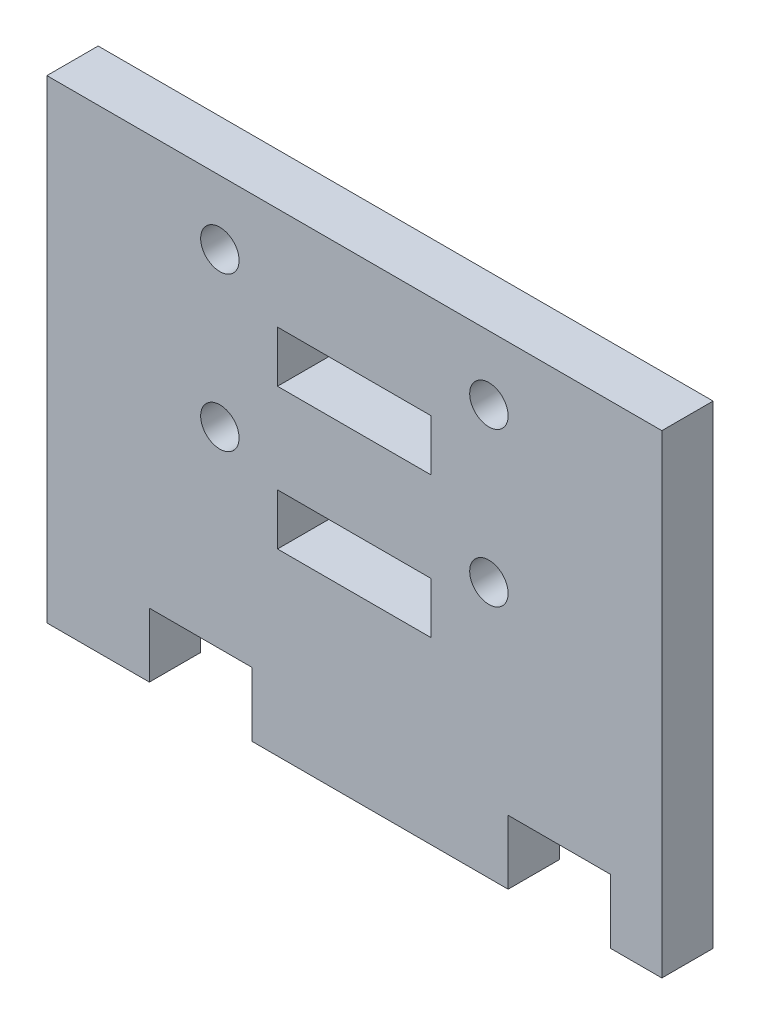
SolidWorks part; units mm, degrees
ref_plane "Front Plane" through (0, 0, 0) normal (0, 0, 1) x (1, 0, 0)
ref_plane "Top Plane" through (0, 0, 0) normal (0, 1, 0) x (1, 0, 0)
ref_plane "Right Plane" through (0, 0, 0) normal (1, 0, 0) x (0, 0, -1)
sketch "Sketch1" plane through (0, 0, 0) normal (0, 0, 1) x (1, 0, 0)
  line L0 (4, 2.5) -> (8, 2.5)
  line L1 (4, 0) -> (0, 0)
  line L2 (0, 18.5) -> (24, 18.5)
  line L3 (0, 0) -> (0, 18.5)
  line L4 (9, 14.5) -> (9, 12.5)
  line L5 (15, 14.5) -> (9, 14.5)
  line L6 (9, 12.5) -> (15, 12.5)
  line L7 (15, 12.5) -> (15, 14.5)
  line L8 (4, 2.5) -> (4, 0)
  line L9 (22, 0) -> (24, 0)
  line L10 (24, 0) -> (24, 18.5)
  line L11 (18, 0) -> (18, 2.5)
  line L12 (15, 7) -> (15, 9)
  line L13 (9, 7) -> (15, 7)
  line L14 (22, 2.5) -> (22, 0)
  line L15 (15, 9) -> (9, 9)
  line L16 (9, 9) -> (9, 7)
  line L17 (18, 2.5) -> (22, 2.5)
  line L18 (8, 0) -> (8, 2.5)
  line L19 (8, 0) -> (18, 0)
  line L20 (12, 12.5) -> (12, 9) construction
  circle A0 centre (6.75, 16) radius 0.75
  circle A1 centre (17.25, 10) radius 0.75
  circle A2 centre (17.25, 16) radius 0.75
  circle A3 centre (6.75, 10) radius 0.75
  dimension "D2" = 4
  dimension "D3" = 18
  dimension "D4" = 2.5
  dimension "D5" = 2
  dimension "D1" = 1.5
  dimension "D6" = 7
  dimension "D7" = 9
  dimension "D8" = 12.5
  dimension "D9" = 15
  dimension "D10" = 6
  dimension "D11" = 10
  dimension "D12" = 18.5
  dimension "D13" = 10.5
extrude "Boss-Extrude1" add sketch "Sketch1" along normal blind 2
equation "\"D13@Sketch1\"= \"fingerWidth@parametersSketch@prostheticParameters.SLDPRT\" - 5.7'Hole distance"
